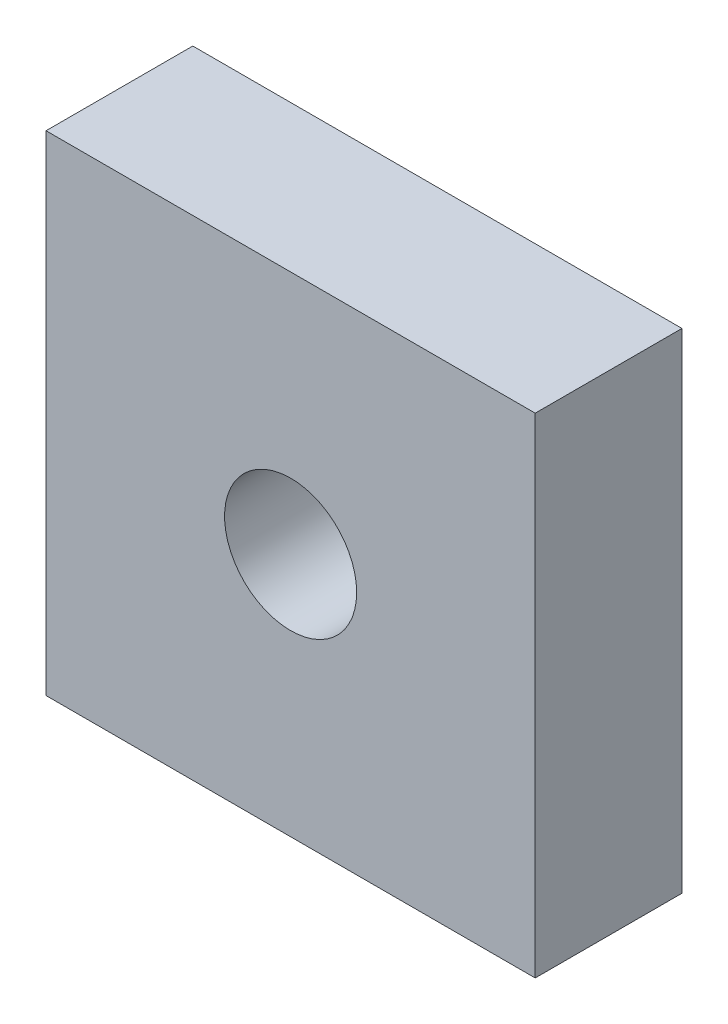
SolidWorks part; units mm, degrees
ref_plane "Front Plane" through (0, 0, 0) normal (0, 0, 1) x (1, 0, 0)
ref_plane "Top Plane" through (0, 0, 0) normal (0, 1, 0) x (1, 0, 0)
ref_plane "Right Plane" through (0, 0, 0) normal (1, 0, 0) x (0, 0, -1)
sketch "Sketch1" plane through (0, 0, 0) normal (0, 0, 1) x (1, 0, 0)
  line L1 (-10, 10) -> (10, 10)
  line L2 (-10, 10) -> (-10, -10)
  line L3 (-10, -10) -> (10, -10)
  line L4 (10, 10) -> (10, -10)
  line L5 (-10, 10) -> (10, -10) construction
  line L6 (-10, -10) -> (10, 10) construction
  circle A0 centre (0, 0) radius 2.7
  point P0 (0, 0)
  dimension "D3" = 5.4
  dimension "D1" = 20
  dimension "D2" = 20
extrude "Boss-Extrude1" add sketch "Sketch1" along normal blind 6
